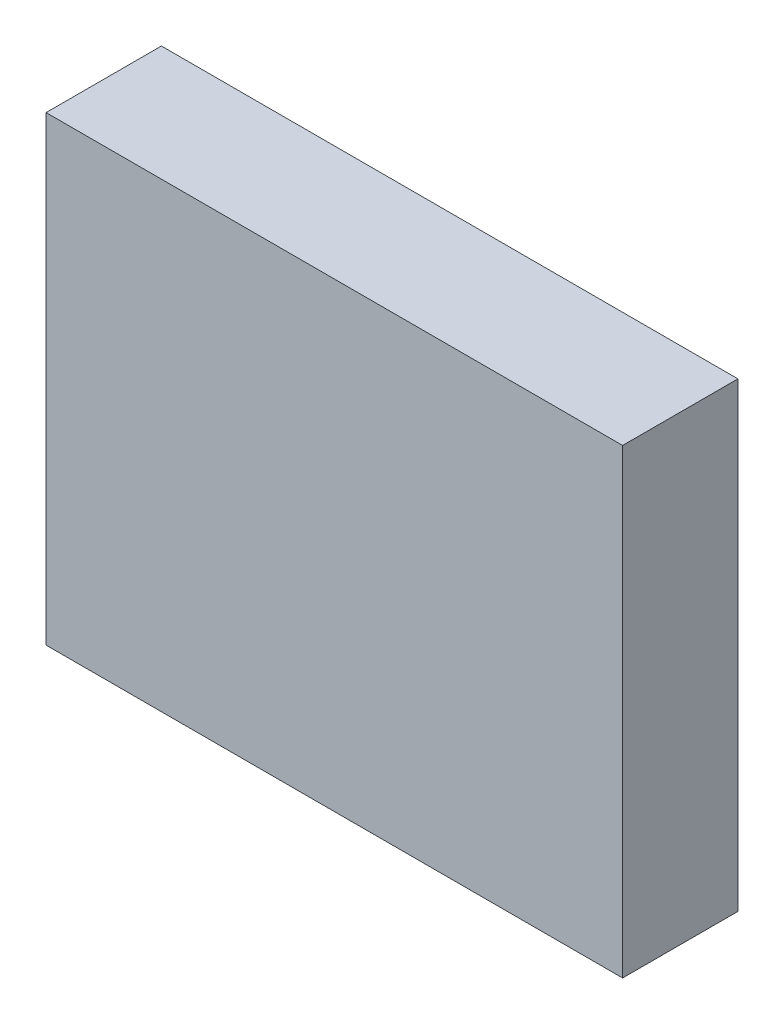
SolidWorks part; units mm, degrees
ref_plane "前视基准面" through (0, 0, 0) normal (0, 0, 1) x (1, 0, 0)
ref_plane "上视基准面" through (0, 0, 0) normal (0, 1, 0) x (1, 0, 0)
ref_plane "右视基准面" through (0, 0, 0) normal (1, 0, 0) x (0, 0, -1)
other "Configuration Table"
sketch "草图1" plane through (0, 0, 0) normal (0, 0, 1) x (1, 0, 0)
  line L1 (0, 0) -> (100, 0)
  line L2 (0, 0) -> (0, 80)
  line L3 (0, 80) -> (100, 80)
  line L4 (100, 0) -> (100, 80)
extrude "凸台-拉伸1" add sketch "草图1" along normal blind 20
